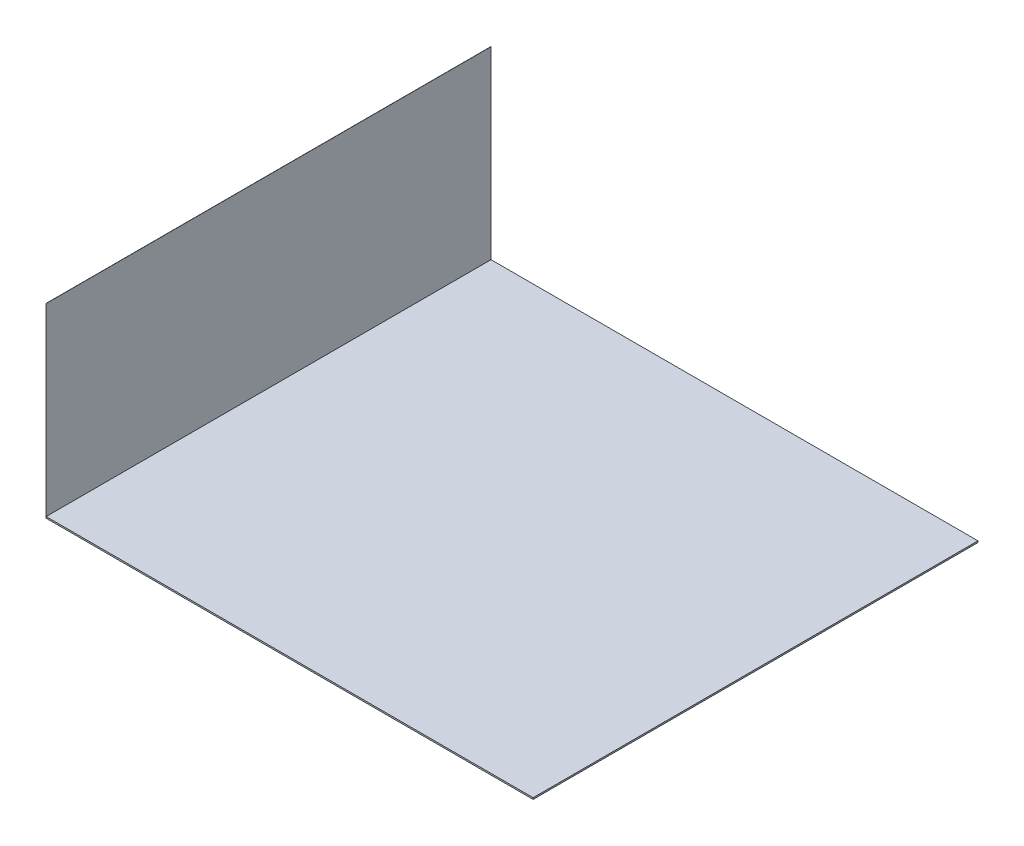
SolidWorks part; units mm, degrees
ref_plane "Front Plane" through (0, 0, 0) normal (0, 0, 1) x (1, 0, 0)
ref_plane "Top Plane" through (0, 0, 0) normal (0, 1, 0) x (1, 0, 0)
ref_plane "Right Plane" through (0, 0, 0) normal (1, 0, 0) x (0, 0, -1)
sketch "Sketch4" plane through (0, 0, 0) normal (1, 0, 0) x (0, 0, -1)
  line L0 (546.1, 3041.65) -> (6985, 3041.65)
  line L1 (0, 0) -> (838.2, 0)
  line L2 (0, 0) -> (0, 2025.65)
  line L3 (0, 2025.65) -> (7518.4, 2025.65)
  line L4 (7518.4, 0) -> (7518.4, 2025.65)
  line L5 (0, 2025.65) -> (7518.4, 2025.65)
  line L6 (0, 2025.65) -> (0, 3117.85)
  line L7 (0, 3117.85) -> (7518.4, 3117.85)
  line L8 (7518.4, 2025.65) -> (7518.4, 3117.85)
  line L9 (838.2, 0) -> (6680.2, 0)
  line L10 (0, 0) -> (0, 889)
  line L11 (838.2, 889) -> (6680.2, 889)
  line L12 (7518.4, 0) -> (7518.4, 889)
  line L13 (0, 0) -> (838.2, 0)
  line L14 (0, 0) -> (0, 2025.65)
  line L15 (0, 2025.65) -> (838.2, 2025.65)
  line L16 (838.2, 889) -> (838.2, 2025.65)
  line L17 (7518.4, 0) -> (6680.2, 0)
  line L18 (7518.4, 0) -> (7518.4, 2025.65)
  line L19 (7518.4, 2025.65) -> (6680.2, 2025.65)
  line L20 (6680.2, 889) -> (6680.2, 2025.65)
  line L21 (7518.4, 889) -> (6680.2, 889)
  line L22 (546.1, 2101.85) -> (6985, 2101.85)
  line L23 (6680.2, 889) -> (6680.2, 0)
  line L24 (76.2, 3041.65) -> (7442.2, 3041.65) construction
  line L25 (3759.2, 2101.85) -> (3949.7, 2101.85)
  line L26 (76.2, 2101.85) -> (7442.2, 2101.85) construction
  line L27 (7442.2, 2101.85) -> (7442.2, 3041.65) construction
  line L28 (3949.7, 2101.85) -> (3568.7, 2101.85)
  line L29 (3949.7, 2101.85) -> (3949.7, 3041.65)
  line L30 (3949.7, 3041.65) -> (3568.7, 3041.65)
  line L31 (3568.7, 2101.85) -> (3568.7, 3041.65)
  line L32 (76.2, 2101.85) -> (76.2, 3041.65) construction
  line L33 (0, 889) -> (838.2, 889)
  line L34 (838.2, 889) -> (838.2, 0)
  line L35 (6680.2, 0) -> (7518.4, 0)
  line L37 (0, 0) -> (7518.4, 0)
  line L38 (0, 0) -> (0, -25.4)
  line L39 (0, -25.4) -> (7518.4, -25.4)
  line L40 (7518.4, 0) -> (7518.4, -25.4)
  line L41 (7518.4, -25.4) -> (0, -25.4)
  line L42 (7518.4, -25.4) -> (7518.4, 0)
  line L43 (7518.4, 0) -> (0, 0)
  line L44 (0, -25.4) -> (0, 0)
  arc A0 (546.1, 3041.65) -> (546.1, 2101.85) centre (546.1, 2571.75) ccw
  arc A1 (6985, 3041.65) -> (6985, 2101.85) centre (6972.1236, 2571.75) cw
  arc A2 (546.1, 3117.85) -> (546.1, 2025.65) centre (546.1, 2571.75) ccw
  arc A3 (6985, 3117.85) -> (6985, 2025.65) centre (6972.1488, 2571.75) cw
  dimension "D8" = 381
  dimension "D9" = 190.5
  dimension "D1" = 25.4
  dimension "D2" = 7518.4
  dimension "D4" = 889
  dimension "D5" = 838.2
  dimension "D6" = 838.2
  dimension "D7" = 76.2
extrude "Extrude3" add sketch "Sketch4" along normal blind 8229.6 contours L39 L40 L17 L9 L1 L38
sketch "Sketch6" plane through (0, 0, 0) normal (1, 0, 0) x (0, 0, -1)
  line L1 (0, 0) -> (7518.4, 0)
  line L2 (0, 0) -> (0, 3117.85)
  line L3 (0, 3117.85) -> (7518.4, 3117.85)
  line L4 (7518.4, 0) -> (7518.4, 3117.85)
  dimension "D1" = 3117.85
extrude "Extrude5" add sketch "Sketch6" against normal blind 2.54 separate body
sketch "Sketch7" plane through (0, 0, 0) normal (1, 0, 0) x (0, 0, -1)
  line L0 (6972.3, 2101.85) -> (546.1, 2101.85)
  line L1 (7518.4, 0) -> (7518.4, 3117.85) construction
  line L2 (7518.4, 2025.65) -> (0, 2025.65)
  line L3 (0, 3117.85) -> (0, 0) construction
  line L5 (0, 2025.65) -> (0, 3117.85)
  line L6 (0, 3117.85) -> (7518.4, 3117.85)
  line L7 (7518.4, 2025.65) -> (7518.4, 3117.85)
  line L9 (546.1, 3041.65) -> (6972.3, 3041.65)
  line L11 (7442.2, 2101.85) -> (76.2, 2101.85) construction
  line L12 (76.2, 3041.65) -> (7442.2, 3041.65) construction
  line L13 (7442.2, 2101.85) -> (7442.2, 3041.65) construction
  line L14 (76.2, 2101.85) -> (76.2, 3041.65) construction
  arc A0 (546.1, 3041.65) -> (546.1, 2101.85) centre (546.1, 2571.75) ccw
  arc A1 (6972.3, 3041.65) -> (6972.3, 2101.85) centre (6972.3, 2571.75) cw
  dimension "D1" = 76.2
